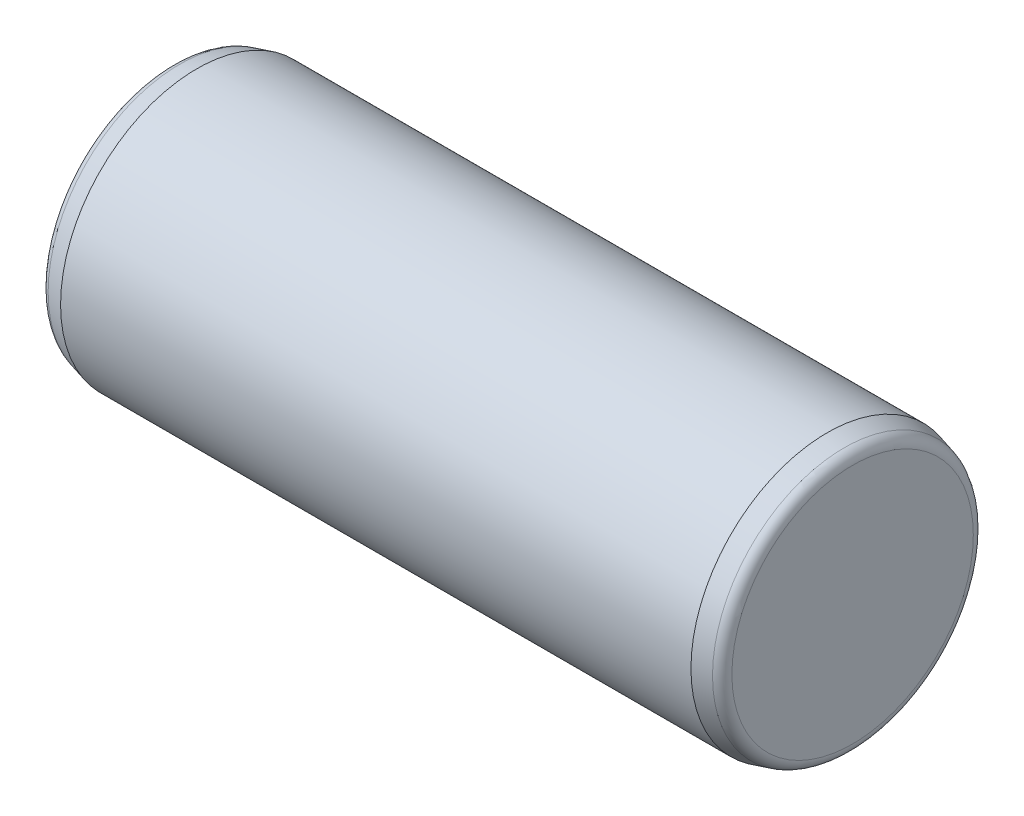
SolidWorks part; units mm, degrees
material "EN36A"
ref_plane "Front Plane" through (0, 0, 0) normal (0, 0, 1) x (1, 0, 0)
ref_plane "Top Plane" through (0, 0, 0) normal (0, 1, 0) x (1, 0, 0)
ref_plane "Right Plane" through (0, 0, 0) normal (1, 0, 0) x (0, 0, -1)
sketch "Sketch1" plane through (0, 0, 0) normal (0, 0, 1) x (1, 0, 0)
  line L0 (0, 0) -> (60.3628, 0) construction
  line L1 (0, 0) -> (0, 5.7)
  line L2 (0, 5.7) -> (1.1196, 6)
  line L3 (1.1196, 6) -> (28.8804, 6)
  line L4 (28.8804, 6) -> (30, 5.7)
  line L5 (30, 5.7) -> (30, 0)
  line L6 (0, 0) -> (30, 0)
  dimension "D1" = 15
  dimension "D2" = 15
  dimension "D3" = 12
  dimension "D4" = 30
  dimension "D5" = 11.4
revolve "Revolve1" add sketch "Sketch1" angle 360 about L0
fillet "Fillet1" radius 0.5 2 edges at (0, 0, 5.7) (30, 0, 5.7)
